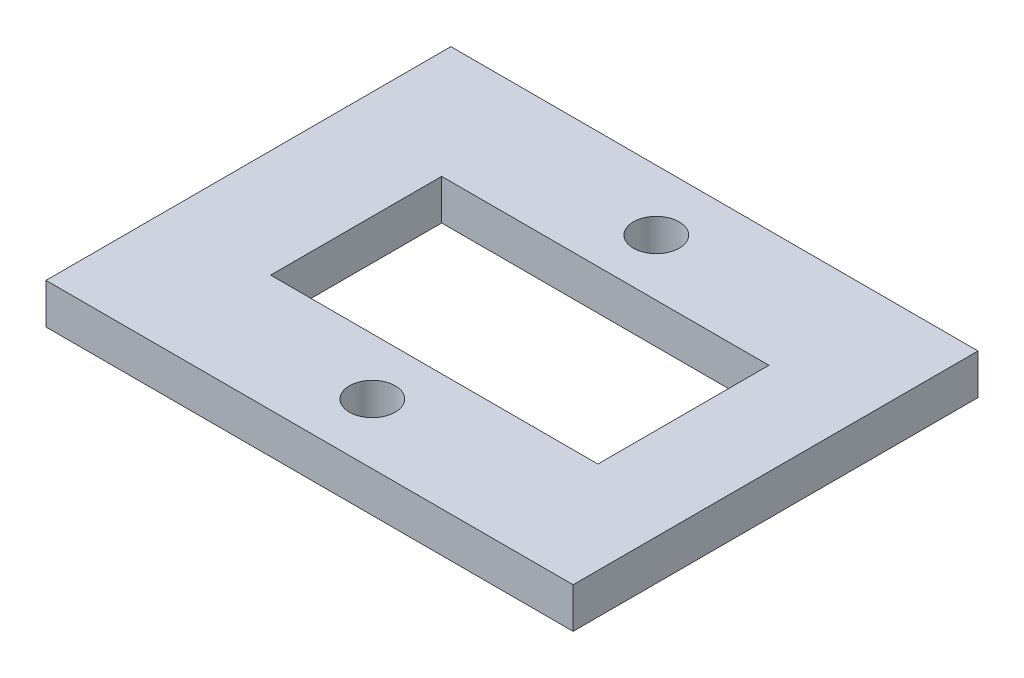
SolidWorks part; units mm, degrees
ref_plane "Front Plane" through (0, 0, 0) normal (0, 0, 1) x (1, 0, 0)
ref_plane "Top Plane" through (0, 0, 0) normal (0, 1, 0) x (1, 0, 0)
ref_plane "Right Plane" through (0, 0, 0) normal (1, 0, 0) x (0, 0, -1)
sketch "Sketch2" plane through (0, 0, 0) normal (0, 1, 0) x (1, 0, 0)
  line L0 (-12.629, 10.7591) -> (11.671, 10.7591)
  line L1 (-20.629, 19.4421) -> (18.5122, 19.4421)
  line L2 (-20.629, 19.4421) -> (-20.629, -10.6209)
  line L3 (-20.629, -10.6209) -> (18.5122, -10.6209)
  line L4 (18.5122, 19.4421) -> (18.5122, -10.6209)
  line L10 (11.671, -1.9409) -> (-12.629, -1.9409)
  line L11 (-12.629, -1.9409) -> (-12.629, 10.7591)
  line L13 (11.671, -1.9409) -> (11.671, 10.7591)
  circle A0 centre (-0.8878, 14.9544) radius 1.7
  circle A1 centre (-0.8878, -6.1332) radius 1.7
  dimension "D8" = 3.4
  dimension "D13" = 19.4
  dimension "D14" = 19.4
  dimension "D2" = 8.68
  dimension "D3" = 12.7
  dimension "D4" = 24.3
  dimension "D5" = 12.7
  dimension "D7" = 4.4877
  dimension "D9" = 8.683
  dimension "D10" = 4.4877
  dimension "D11" = 8
extrude "Boss-Extrude1" add sketch "Sketch2" along normal mid plane 3
